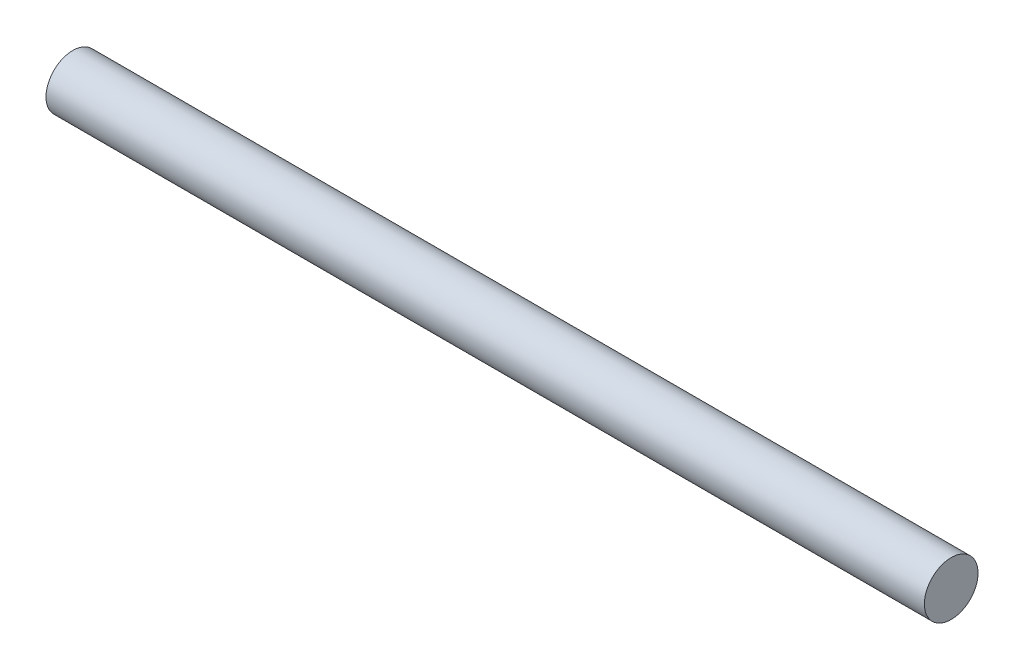
SolidWorks part; units mm, degrees
material "Kiefer"
ref_plane "Ebene vorne" through (0, 0, 0) normal (0, 0, 1) x (1, 0, 0)
ref_plane "Ebene oben" through (0, 0, 0) normal (0, 1, 0) x (1, 0, 0)
ref_plane "Ebene rechts" through (0, 0, 0) normal (1, 0, 0) x (0, 0, -1)
sketch "Skizze1" plane through (0, 0, 0) normal (1, 0, 0) x (0, 0, -1)
  circle A0 centre (0, 0) radius 11
  dimension "D1" = 22
extrude "Aufsatz-Linear austragen1" add sketch "Skizze1" along normal blind 360
